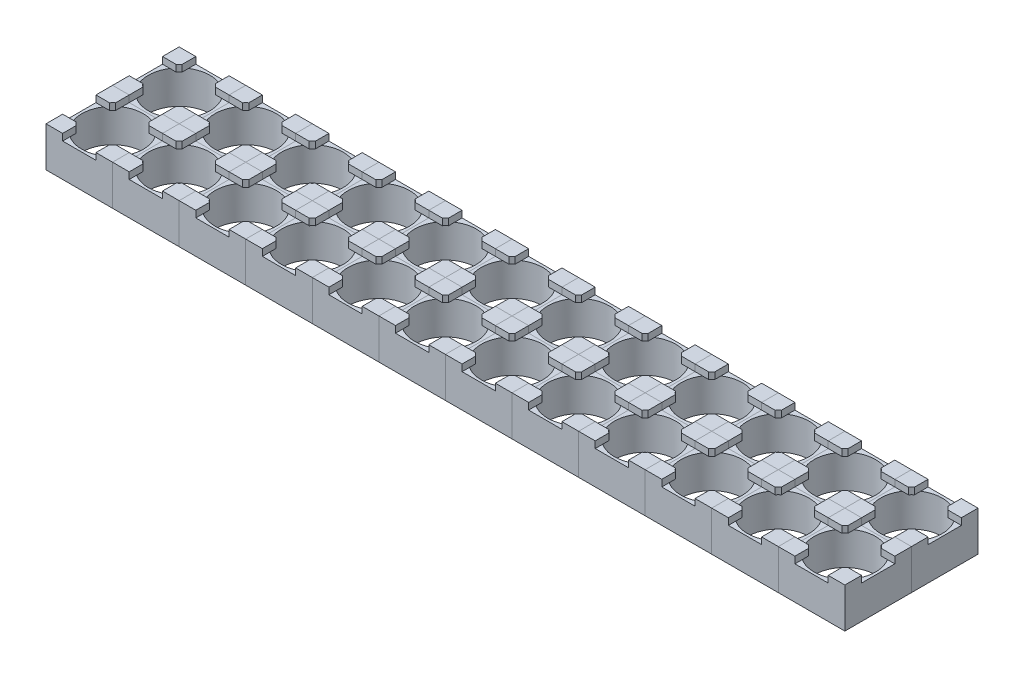
SolidWorks part; units mm, degrees
ref_plane "정면" through (0, 0, 0) normal (0, 0, 1) x (1, 0, 0)
ref_plane "윗면" through (0, 0, 0) normal (0, 1, 0) x (1, 0, 0)
ref_plane "우측면" through (0, 0, 0) normal (1, 0, 0) x (0, 0, -1)
sketch "스케치1" plane through (0, 0, 0) normal (0, 1, 0) x (1, 0, 0)
  line L1 (-10, 10) -> (10, 10)
  line L2 (-10, 10) -> (-10, -10)
  line L3 (-10, -10) -> (10, -10)
  line L4 (10, 10) -> (10, -10)
  line L5 (-10, 10) -> (10, -10) construction
  line L6 (-10, -10) -> (10, 10) construction
  circle A0 centre (0, 0) radius 9.25
  dimension "D1" = 18.5
  dimension "Size" = 20
extrude "보스-돌출1" add sketch "스케치1" along normal blind 10
sketch "스케치2" plane through (0, 10, 0) normal (0, 1, 0) x (1, 0, 0)
  line L0 (0, 0) -> (0, 10) construction
  line L1 (-10, 10) -> (-5, 10)
  line L2 (-10, 10) -> (-10, 5)
  line L3 (-10, 5) -> (-5, 5)
  line L4 (-5, 10) -> (-5, 5)
  line L6 (10, 10) -> (-10, 10) construction
  line L8 (10, 10) -> (10, 5)
  line L9 (10, 10) -> (5, 10)
  line L10 (5, 10) -> (5, 5)
  line L11 (10, 5) -> (5, 5)
  line L12 (10, -10) -> (5, -10)
  line L13 (10, -10) -> (10, -5)
  line L14 (10, -5) -> (5, -5)
  line L15 (5, -10) -> (5, -5)
  line L16 (-10, -10) -> (-10, -5)
  line L17 (-10, -10) -> (-5, -10)
  line L18 (-5, -10) -> (-5, -5)
  line L19 (-10, -5) -> (-5, -5)
  circle A0 centre (0, 0) radius 7.75
  circle A1 centre (0, 0) radius 9.25 construction
  point P25 (0, 0)
  line M5 (10, -10) -> (10, 10)
  line M6 (10, 10) -> (-10, 10)
  line M7 (-10, 10) -> (-10, -10)
  line M8 (-10, -10) -> (10, -10)
  circle M9 centre (0, 0) radius 9.25
  dimension "D1" = 10
  dimension "D3" = 1.5
  dimension "D2" = 4
extrude "보스-돌출2" add sketch "스케치2" along normal blind 2 contours L4 L3 M6 M7 M9 | A0 L4 L3 M9 | A0 L11 L10 M9 | L11 L10 M5 M6 M9 | A0 L15 L14 M9 | L15 L14 M8 M5 M9 | L19 L18 M7 M8 M9 | A0 L19 L18 M9
pattern_linear "선형 패턴1" count 12 spacing 20 along (1, 0, 0) count 2 spacing 20 along (0, 0, -1) of bodies 102
equation "\"Size\"= \"Size@스케치1\""
equation "\"D3@선형 패턴1\"=\"Size\""
equation "\"D1@선형 패턴1\" = \"parallel@Battery Pack.Assembly\""
equation "\"D4@선형 패턴1\"=\"Size\""
equation "\"D2@선형 패턴1\"=\"Vertical@Battery Pack.Assembly\""
